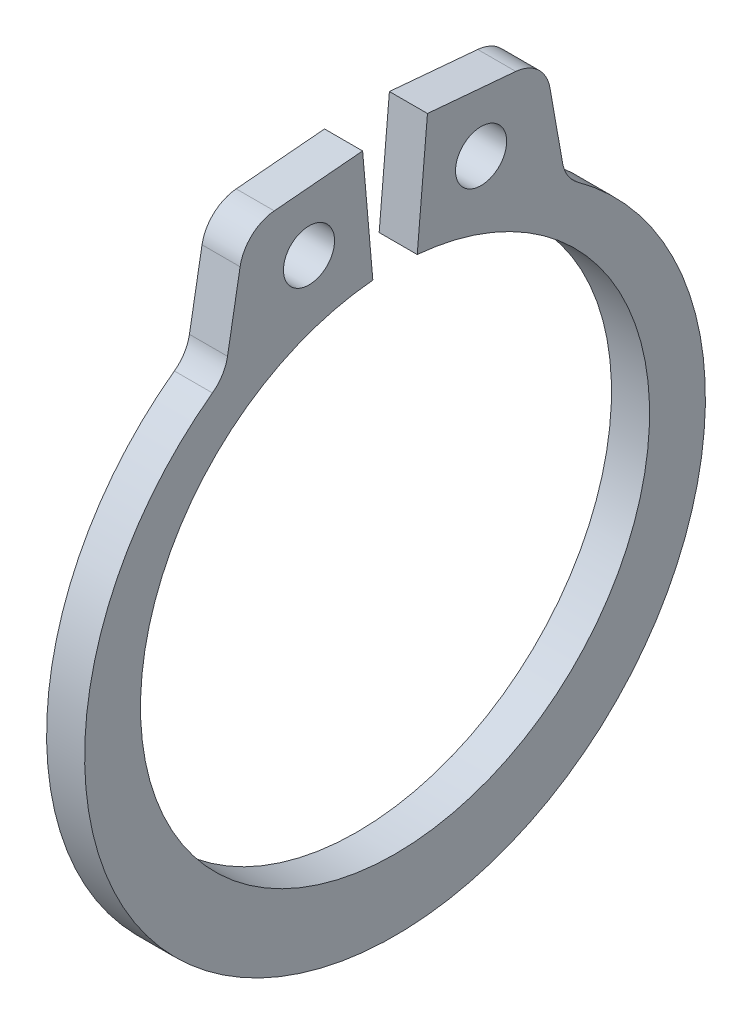
SolidWorks part; units mm, degrees
ref_plane "Front" through (0, 0, 0) normal (0, 0, 1) x (1, 0, 0)
ref_plane "Top" through (0, 0, 0) normal (0, 1, 0) x (1, 0, 0)
ref_plane "Right" through (0, 0, 0) normal (1, 0, 0) x (0, 0, -1)
sketch "Sketch1" plane through (0, 0, 0) normal (1, 0, 0) x (0, 0, -1)
  line L0 (0, 0) -> (0, 5.9436) construction
  line L1 (-0.518, 5.921) -> (-0.7571, 8.6537)
  line L2 (-0.7571, 8.6537) -> (-3.4993, 8.4138) construction
  line L3 (-3.4993, 8.4138) -> (-3.9756, 5.7123) construction
  line L4 (0.7571, 8.6537) -> (0.518, 5.921)
  line L5 (0.7571, 8.6537) -> (3.4993, 8.4138) construction
  line L6 (3.4993, 8.4138) -> (3.9756, 5.7123) construction
  line L7 (-3.9756, 5.7123) -> (-3.3952, 4.8784) construction
  line L8 (3.9756, 5.7123) -> (3.3952, 4.8784) construction
  line L9 (0, -5.9436) -> (0, -7.5946) construction
  line L10 (-3.4993, 8.4138) -> (-0.518, 5.921) construction
  line L11 (-5.9436, 0) -> (5.9436, 0) construction
  line L12 (0, 5.9436) -> (0, 8.6868) construction
  line L13 (3.4993, 8.4138) -> (3.9756, 5.7123)
  line L14 (-3.4993, 8.4138) -> (-3.9756, 5.7123)
  line L15 (0.7571, 8.6537) -> (3.4993, 8.4138)
  line L16 (-0.7571, 8.6537) -> (-3.4993, 8.4138)
  circle A0 centre (0, 0) radius 5.9436 construction
  arc A1 (-0.518, 5.921) -> (0.518, 5.921) centre (0, 0) ccw
  circle A2 centre (0, -0.3473) radius 7.2473 construction
  circle A3 centre (0, 0) radius 7.2898 construction
  circle A4 centre (-2.0086, 7.1674) radius 0.5969
  circle A5 centre (2.0086, 7.1674) radius 0.5969
  arc A6 (-3.9756, 5.7123) -> (3.9756, 5.7123) centre (0, -0.3473) ccw
  dimension "D1" = 15
  dimension "A" = 11.8872
  dimension "L" = 14.5796
  dimension "Hole" = 1.1938
  dimension "Smin" = 1.016
  dimension "Smax" = 1.651
  dimension "H" = 2.7432
  dimension "Angle" = 5
extrude "Extrude1" add sketch "Sketch1" along normal mid plane 0.889
fillet "Fillet1" radius 0.889 4 edges at (0, 5.7123, 3.9756) (0, 5.7123, -3.9756) (0, 8.4138, -3.4993) (0, 8.4138, 3.4993)
sketch "Sketch2" plane through (0, 0, 0) normal (0, 0, 1) x (1, 0, 0)
  line L0 (-2.54, 0) -> (7.62, 0)
  line L1 (7.62, 0) -> (7.62, -6.35)
  line L3 (7.62, -6.35) -> (0.508, -6.35)
  line L4 (0.508, -6.35) -> (0.508, -5.9436)
  line L5 (0.508, -5.9436) -> (-0.508, -5.9436)
  line L6 (-0.508, -5.9436) -> (-0.508, -6.35)
  line L7 (-0.508, -6.35) -> (-2.54, -6.35) construction
  line L8 (-2.54, -6.35) -> (-2.54, 0) construction
  line L9 (0, -5.9436) -> (0, 0) construction
  line L10 (7.62, 0) -> (14.0551, 0) construction
  line L11 (-0.508, -6.35) -> (-2.3368, -6.35)
  line L12 (-2.3368, -6.35) -> (-2.54, -6.1468)
  line L13 (-2.54, -6.1468) -> (-2.54, 0)
  point P14 (-0.508, -6.1468)
  dimension "D2" = 10.16
  dimension "D3" = 2.54
  dimension "D4" = 45
revolve "Revolve1" [suppressed] add sketch "Sketch2" angle 360 about L10
equation "\"D2@Sketch2\" = \"W@Sketch2\"*10"
equation "\"D3@Sketch2\" = \"D2@Sketch2\"/4"
equation "\"D1@Fillet1\" = \"D1@Extrude1\""
